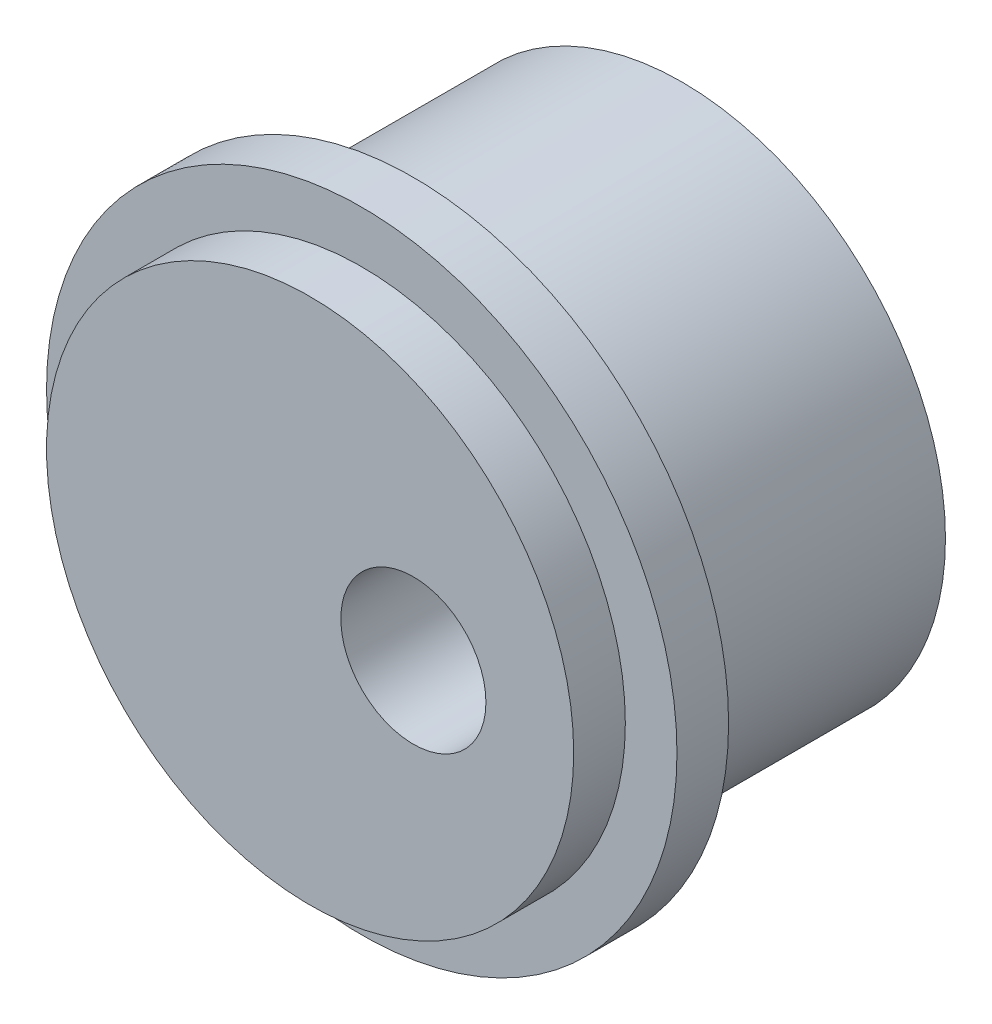
SolidWorks part; units mm, degrees
ref_plane "Front Plane" through (0, 0, 0) normal (0, 0, 1) x (1, 0, 0)
ref_plane "Top Plane" through (0, 0, 0) normal (0, 1, 0) x (1, 0, 0)
ref_plane "Right Plane" through (0, 0, 0) normal (1, 0, 0) x (0, 0, -1)
ref_plane "Motor-Start" through (0, 0, 20) normal (0, 0, 1) x (1, 0, 0)
sketch "Sketch5" plane through (0, 0, 20) normal (0, 0, 1) x (1, 0, 0)
  line L0 (5.95, 14.05) -> (34.05, -14.05) construction
  line L1 (5.95, 14.05) -> (34.05, 14.05)
  line L2 (5.95, 14.05) -> (5.95, -14.05)
  line L3 (5.95, -14.05) -> (34.05, -14.05)
  line L4 (34.05, 14.05) -> (34.05, -14.05)
  line L5 (-1.05, 21.05) -> (-1.05, -21.05)
  line L6 (-1.05, -21.05) -> (41.05, -21.05)
  line L7 (41.05, 21.05) -> (41.05, -21.05)
  line L8 (-1.05, 21.05) -> (41.05, 21.05)
  point P9 (20, 0)
  dimension "D1" = 28.1
  dimension "D2" = 7
  dimension "D3" = 20
extrude "Boss-Extrude3" add sketch "Sketch5" along normal blind 32 separate body
sketch "Sketch6" plane through (0, 21.05, 0) normal (0, 1, 0) x (1, 0, 0)
  line L5 (41.05, -20) -> (-1.05, -20) construction
  line L6 (41.05, -20) -> (-1.05, -20) construction
  line L7 (12.5, -22.5) -> (27.5, -22.5)
  line L8 (12.5, -22.5) -> (12.5, -32.5)
  line L9 (12.5, -32.5) -> (27.5, -32.5)
  line L10 (27.5, -22.5) -> (27.5, -32.5)
  point P4 (20, -22.5)
  point P5 (20, -20)
  dimension "D1" = 10
  dimension "D2" = 15
  dimension "D3" = 2.5
extrude "Cut-Extrude2" cut sketch "Sketch6" against normal up to next
sketch "Sketch7" plane through (0, 0, 52) normal (0, 0, 1) x (1, 0, 0)
  line L0 (34.05, -14.05) -> (34.05, 14.05) construction
  line L1 (5.95, 14.05) -> (5.95, -14.05) construction
  line L2 (5.95, -14.05) -> (34.05, -14.05) construction
  line L6 (41.05, 21.05) -> (-1.05, 21.05)
  line L7 (-1.05, 21.05) -> (-1.05, -21.05)
  line L8 (-1.05, -21.05) -> (41.05, -21.05)
  line L9 (41.05, -21.05) -> (41.05, 21.05)
  line L10 (41.05, 21.05) -> (-1.05, 21.05)
  line L11 (-1.05, 21.05) -> (-1.05, -21.05)
  line L12 (-1.05, -21.05) -> (41.05, -21.05)
  line L13 (41.05, -21.05) -> (41.05, 21.05)
  circle A0 centre (20, 0) radius 14.05
  point P3 (0, 0)
  dimension "D1" = 0
extrude "Boss-Extrude4" add sketch "Sketch7" along normal blind 40
sketch "Sketch11" plane through (0, 0, 92) normal (0, 0, 1) x (1, 0, 0)
  line L4 (41.05, -21.05) -> (41.05, 21.05)
  line L5 (41.05, 21.05) -> (-1.05, 21.05)
  line L6 (-1.05, 21.05) -> (-1.05, -21.05)
  line L7 (-1.05, -21.05) -> (41.05, -21.05)
  line L9 (20, 21.05) -> (-1.05, 21.05)
  line L10 (-1.05, 21.05) -> (-1.05, 0)
  arc A0 (20, 21.05) -> (-1.05, 0) centre (20, 0) ccw
  circle A1 centre (20, 0) radius 14.05 construction
  circle A2 centre (20, 0) radius 14.05 construction
  point P1 (0, 0)
  dimension "D1" = 0
extrude "Cut-Extrude3" cut sketch "Sketch11" against normal up to surface (72 mm away)
pattern_circular "CirPattern1" count 4 over 360 about axis through (20, 0, 92) along (0, 0, 1) of "Cut-Extrude3"
sketch "Sketch24" plane through (0, 0, 92) normal (0, 0, 1) x (1, 0, 0)
  line L0 (41.05, 0) -> (41.05, 40.0098) construction
  line L1 (51.05, 0) -> (51.05, 27.3225) construction
  circle A0 centre (0, 0) radius 51.05
  circle A2 centre (20, 0) radius 21.05 construction
  circle A3 centre (20, 0) radius 21.05
  dimension "D1" = 10
extrude "Boss-Extrude6" add sketch "Sketch24" against normal up to surface (72 mm away) up to face at (20, 0, 20)
sketch "Sketch25" plane through (0, 0, 92) normal (0, 0, 1) x (1, 0, 0)
  circle A0 centre (0, 0) radius 61.05
  circle A1 centre (0, 0) radius 51.05
  circle A2 centre (0, 0) radius 51.05
  dimension "D1" = 0
  dimension "D2" = 10
extrude "Boss-Extrude7" add sketch "Sketch25" against normal blind 10 from offset 10
